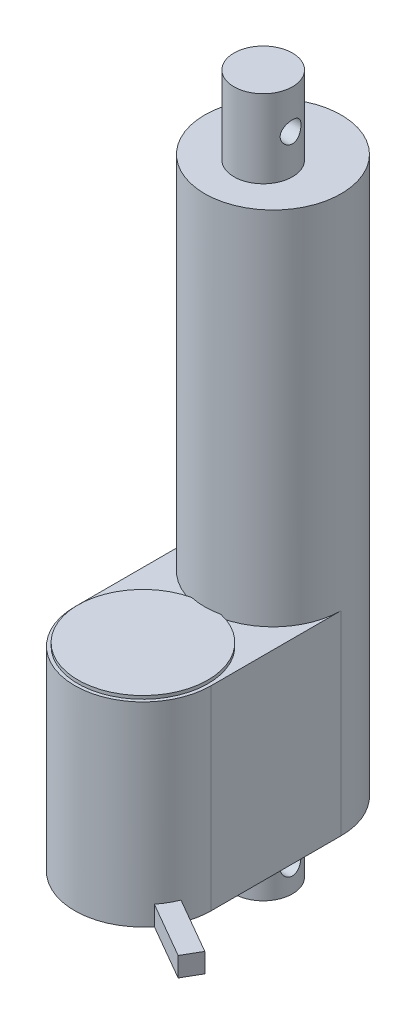
SolidWorks part; units mm, degrees
ref_plane "Front" through (0, 0, 0) normal (0, 0, 1) x (1, 0, 0)
ref_plane "Top" through (0, 0, 0) normal (0, 1, 0) x (1, 0, 0)
ref_plane "Right" through (0, 0, 0) normal (1, 0, 0) x (0, 0, -1)
sketch "Sketch1" plane through (0, 0, 0) normal (0, 1, 0) x (1, 0, 0)
  line L0 (0, 0) -> (0, -40) construction
  line L1 (21, 0) -> (21, -40)
  line L2 (-21, 0) -> (-21, -40)
  line L3 (0, 21) -> (0, -61) construction
  arc A0 (21, 0) -> (-21, 0) centre (0, 0) ccw
  arc A1 (-21, -40) -> (21, -40) centre (0, -40) ccw
  point P3 (0, -20)
  dimension "D1" = 42
  dimension "D2" = 82
extrude "Boss-Extrude1" add sketch "Sketch1" along normal blind 60
sketch "Sketch2" plane through (0, 60, 0) normal (0, 1, 0) x (1, 0, 0)
  circle A0 centre (0, -40) radius 20
  arc A1 (-21, -40) -> (21, -40) centre (0, -40) ccw construction
  dimension "D1" = 40
extrude "Boss-Extrude2" add sketch "Sketch2" along normal blind 1
sketch "Sketch3" plane through (0, 60, 0) normal (0, 1, 0) x (1, 0, 0)
  circle A0 centre (0, 0) radius 21
  arc A2 (21, 0) -> (-21, 0) centre (0, 0) ccw construction
extrude "Boss-Extrude3" add sketch "Sketch3" along normal offset from surface (111.072 mm away) 171.072 up to face at (0, 0, 20)
sketch "Sketch4" plane through (0, 0, 0) normal (0, -1, 0) x (1, 0, 0)
  line L0 (0, -21) -> (0, 3) construction
  circle A0 centre (0, 3) radius 9
  arc A1 (-21, 0) -> (21, 0) centre (0, 0) ccw construction
  point P7 (0, -21)
  dimension "D1" = 18
  dimension "D2" = 24
extrude "Boss-Extrude4" add sketch "Sketch4" along normal blind 20
sketch "Sketch5" plane through (-21, 0, 0) normal (-1, 0, 0) x (0, 0, 1)
  line L0 (3, -12) -> (3, -20) construction
  line L1 (-6, -20) -> (12, -20) construction
  line L2 (-21, 0) -> (0, 0) construction
  circle A0 centre (3, -12) radius 3.2
  point P2 (0, 0)
  dimension "D2" = 6.4
  dimension "D1" = 12
extrude "Cut-Extrude1" cut sketch "Sketch5" against normal through all both and the other way through all
sketch "Sketch6" plane through (0, 171.072, 0) normal (0, 1, 0) x (1, 0, 0)
  circle A0 centre (0, -3) radius 9
  circle A1 centre (0, -3) radius 9 construction
extrude "Boss-Extrude5" add sketch "Sketch6" along normal blind 24
sketch "Sketch7" plane through (-21, 0, 0) normal (-1, 0, 0) x (0, 0, 1)
  line L0 (21, 171.072) -> (-21, 171.072) construction
  line L1 (3, 183.072) -> (3, 195.072) construction
  line L2 (12, 195.072) -> (-6, 195.072) construction
  circle A0 centre (3, 183.072) radius 3.2
  point P4 (0, 0)
  dimension "D2" = 6.4
  dimension "D1" = 12
extrude "Cut-Extrude2" cut sketch "Sketch7" against normal through all both and the other way through all
sketch "Sketch8" plane through (0, 0, 0) normal (0, -1, 0) x (1, 0, 0)
  line L0 (19.5, 47.7942) -> (36.8205, 57.7942)
  line L1 (36.8205, 57.7942) -> (33.8205, 62.9904)
  line L2 (33.8205, 62.9904) -> (16.5, 52.9904)
  line L3 (16.5, 52.9904) -> (19.5, 47.7942)
  line L4 (-21, 0) -> (-21, 40) construction
  line L5 (18, 50.3923) -> (0, 40) construction
  arc A0 (21, 40) -> (-21, 40) centre (0, 40) ccw construction
  point P4 (0, 0)
  dimension "D1" = 20
  dimension "D2" = 6
  dimension "D3" = 240
extrude "Boss-Extrude6" add sketch "Sketch8" against normal blind 6
